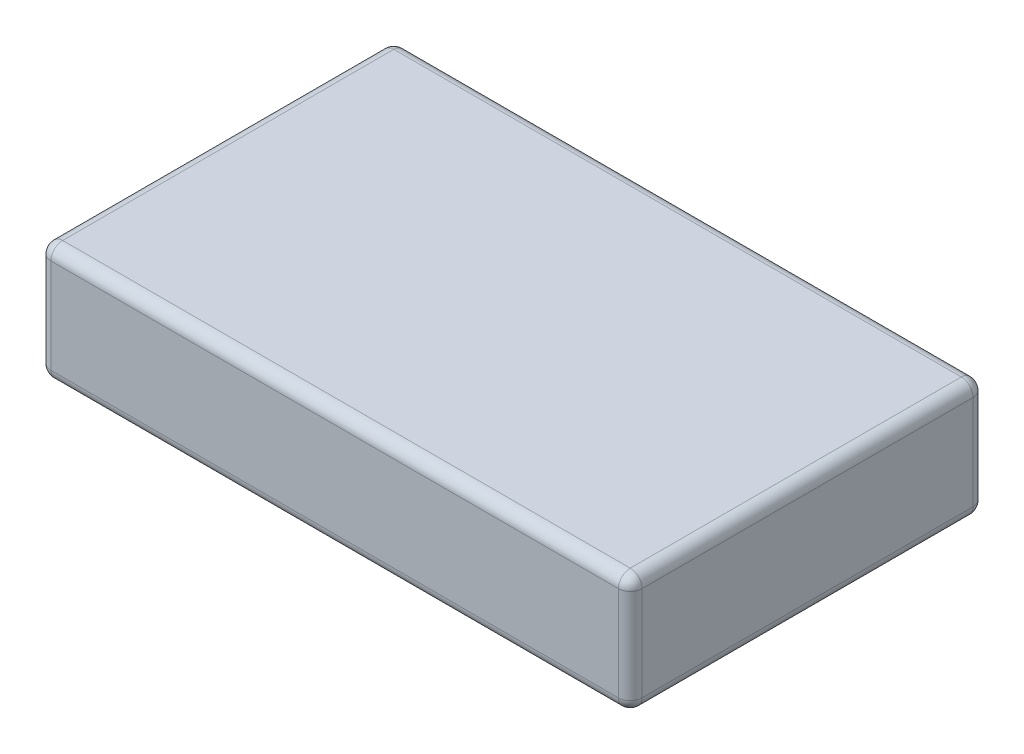
SolidWorks part; units mm, degrees
ref_plane "Front Plane" through (0, 0, 0) normal (0, 0, 1) x (1, 0, 0)
ref_plane "Top Plane" through (0, 0, 0) normal (0, 1, 0) x (1, 0, 0)
ref_plane "Right Plane" through (0, 0, 0) normal (1, 0, 0) x (0, 0, -1)
sketch "Sketch1" plane through (0, 0, 0) normal (0, 1, 0) x (1, 0, 0)
  line L0 (-25, 0) -> (25, 0) construction
  line L1 (-25, -15) -> (25, -15)
  line L2 (-25, -15) -> (-25, 15)
  line L3 (-25, 15) -> (25, 15)
  line L4 (25, -15) -> (25, 15)
  point P5 (0, -15)
  point P7 (0, 0)
  dimension "D1" = 50
  dimension "D2" = 30
  dimension "D3" = 25
extrude "Boss-Extrude1" add sketch "Sketch1" along normal blind 10
fillet "Fillet1" radius 1 12 edges at (-25, 5, -15) (-25, 5, 15) (25, 5, 15) (25, 5, -15) (0, 0, 15) (25, 0, 0) (0, 0, -15) (-25, 0, 0) (0, 10, -15) (25, 10, 0) (0, 10, 15) (-25, 10, 0)
